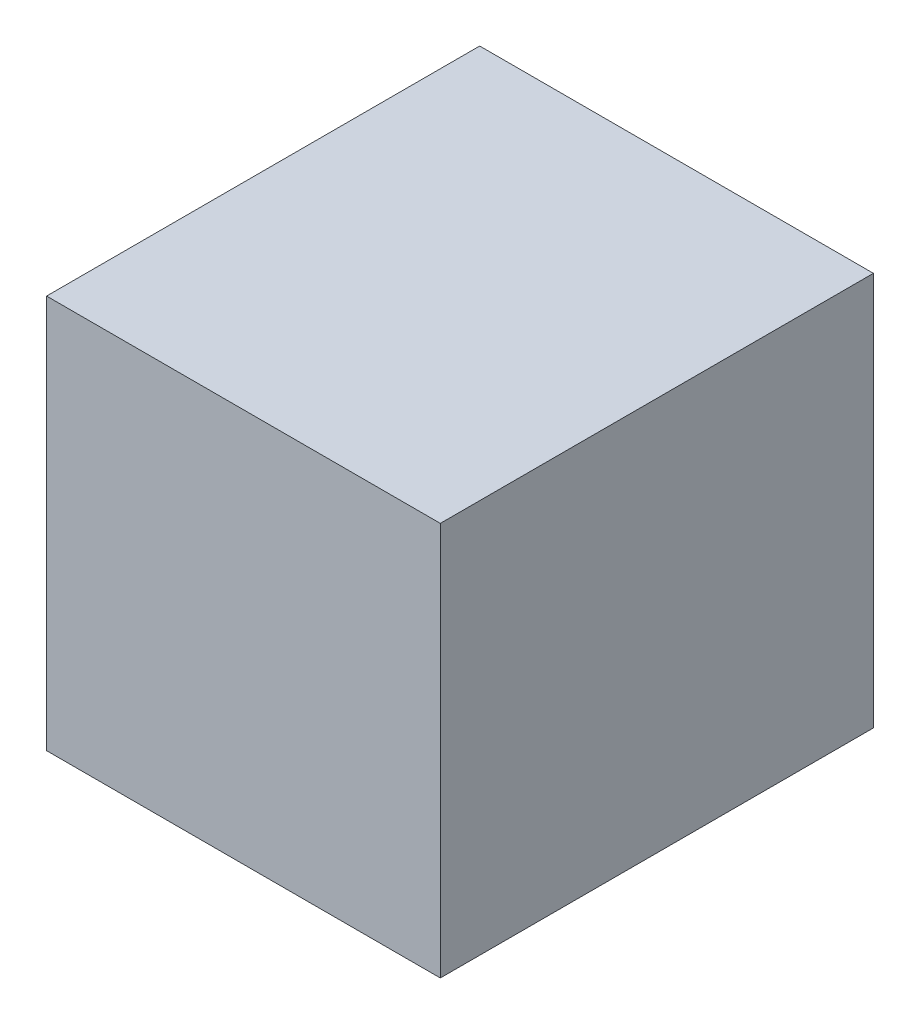
SolidWorks part; units mm, degrees
ref_plane "Front Plane" through (0, 0, 0) normal (0, 0, 1) x (1, 0, 0)
ref_plane "Top Plane" through (0, 0, 0) normal (0, 1, 0) x (1, 0, 0)
ref_plane "Right Plane" through (0, 0, 0) normal (1, 0, 0) x (0, 0, -1)
other "Configuration Table"
sketch "Sketch1" plane through (0, 0, 0) normal (0, 0, 1) x (1, 0, 0)
  line L1 (180, 200) -> (280, 200)
  line L2 (180, 200) -> (180, 300)
  line L3 (180, 300) -> (280, 300)
  line L4 (280, 200) -> (280, 300)
extrude "OVEN_pano_psu_24V_1" add sketch "Sketch1" against normal blind 110 from offset 138 separate body
